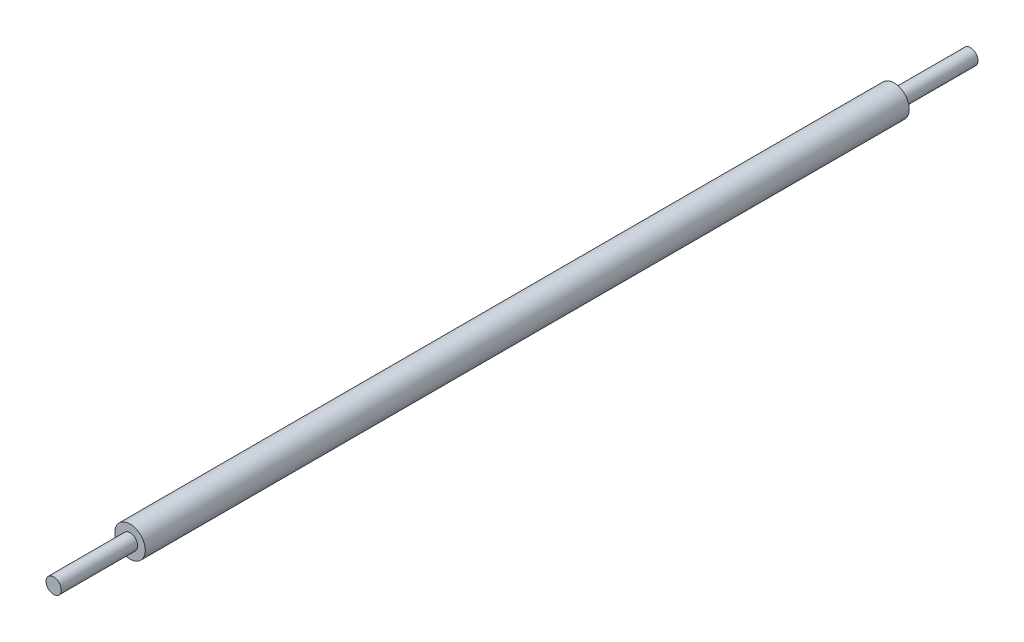
SolidWorks part; units mm, degrees
ref_plane "Alzado" through (0, 0, 0) normal (0, 0, 1) x (1, 0, 0)
ref_plane "Planta" through (0, 0, 0) normal (0, 1, 0) x (1, 0, 0)
ref_plane "Vista lateral" through (0, 0, 0) normal (1, 0, 0) x (0, 0, -1)
sketch "Croquis1" plane through (0, 0, 0) normal (0, 0, 1) x (1, 0, 0)
  circle A0 centre (0, 0) radius 0.05
  dimension "D1" = 0.1
extrude "Saliente-Extruir1" add sketch "Croquis1" along normal blind 2.5
sketch "Croquis2" plane through (0, 0, 2.5) normal (0, 0, 1) x (1, 0, 0)
  circle A0 centre (0, 0) radius 0.025
  dimension "D1" = 0.05
sketch "Croquis3" plane through (0, 0, 0) normal (0, 0, -1) x (-1, 0, 0)
  circle A0 centre (0, 0) radius 0.025
  dimension "D1" = 0.05
extrude "Saliente-Extruir3" add sketch "Croquis2" along normal blind 0.25
extrude "Saliente-Extruir4" add sketch "Croquis3" along normal blind 0.25
